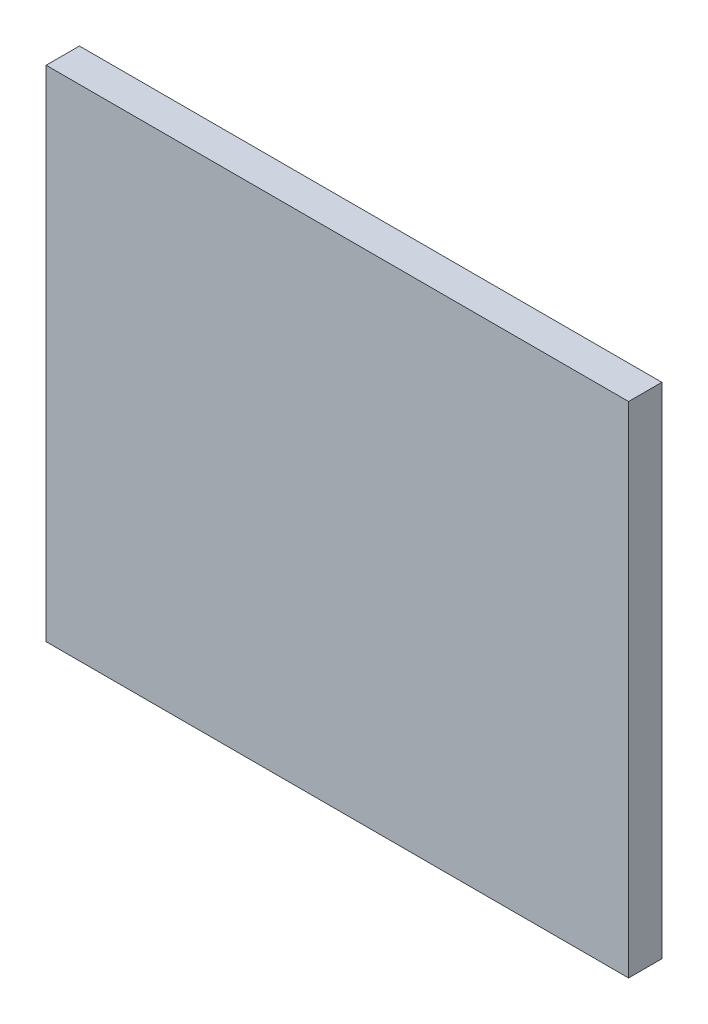
SolidWorks part; units mm, degrees
ref_plane "Front Plane" through (0, 0, 0) normal (0, 0, 1) x (1, 0, 0)
ref_plane "Top Plane" through (0, 0, 0) normal (0, 1, 0) x (1, 0, 0)
ref_plane "Right Plane" through (0, 0, 0) normal (1, 0, 0) x (0, 0, -1)
sketch "Sketch1" plane through (0, 0, 0) normal (0, 0, 1) x (1, 0, 0)
  line L1 (0, 0) -> (70, 0)
  line L2 (0, 0) -> (0, 60)
  line L3 (0, 60) -> (70, 60)
  line L4 (70, 0) -> (70, 60)
  dimension "D1" = 70
  dimension "D2" = 60
extrude "Profile" add sketch "Sketch1" along normal blind 4
equation "\"Profile_Depth\"= 4mm"
equation "\"D1@Profile\" = \"Profile_Depth\""
equation "\"Profile_Sketch_1\"= 70mm"
equation "\"D1@Sketch1\" = \"Profile_Sketch_1\""
equation "\"Profile_Sketch_2\"= 60mm"
equation "\"D2@Sketch1\" = \"Profile_Sketch_2\""
equation "\"EnvelopeWidth\"= 70mm"
equation "\"EnvelopeHeight\"= 60mm"
